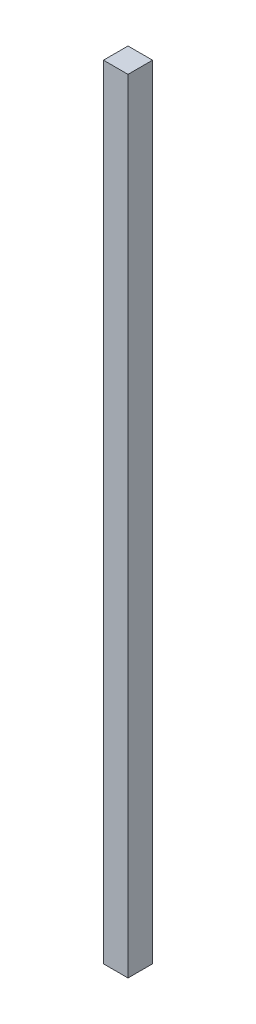
SolidWorks part; units mm, degrees
ref_plane "Front Plane" through (0, 0, 0) normal (0, 0, 1) x (1, 0, 0)
ref_plane "Top Plane" through (0, 0, 0) normal (0, 1, 0) x (1, 0, 0)
ref_plane "Right Plane" through (0, 0, 0) normal (1, 0, 0) x (0, 0, -1)
sketch "Sketch1" plane through (0, 0, 0) normal (0, 1, 0) x (1, 0, 0)
  line L1 (0, 0) -> (20, 0)
  line L2 (0, 0) -> (0, -20)
  line L3 (0, -20) -> (20, -20)
  line L4 (20, 0) -> (20, -20)
extrude "Boss-Extrude1" add sketch "Sketch1" along normal blind 637.76
